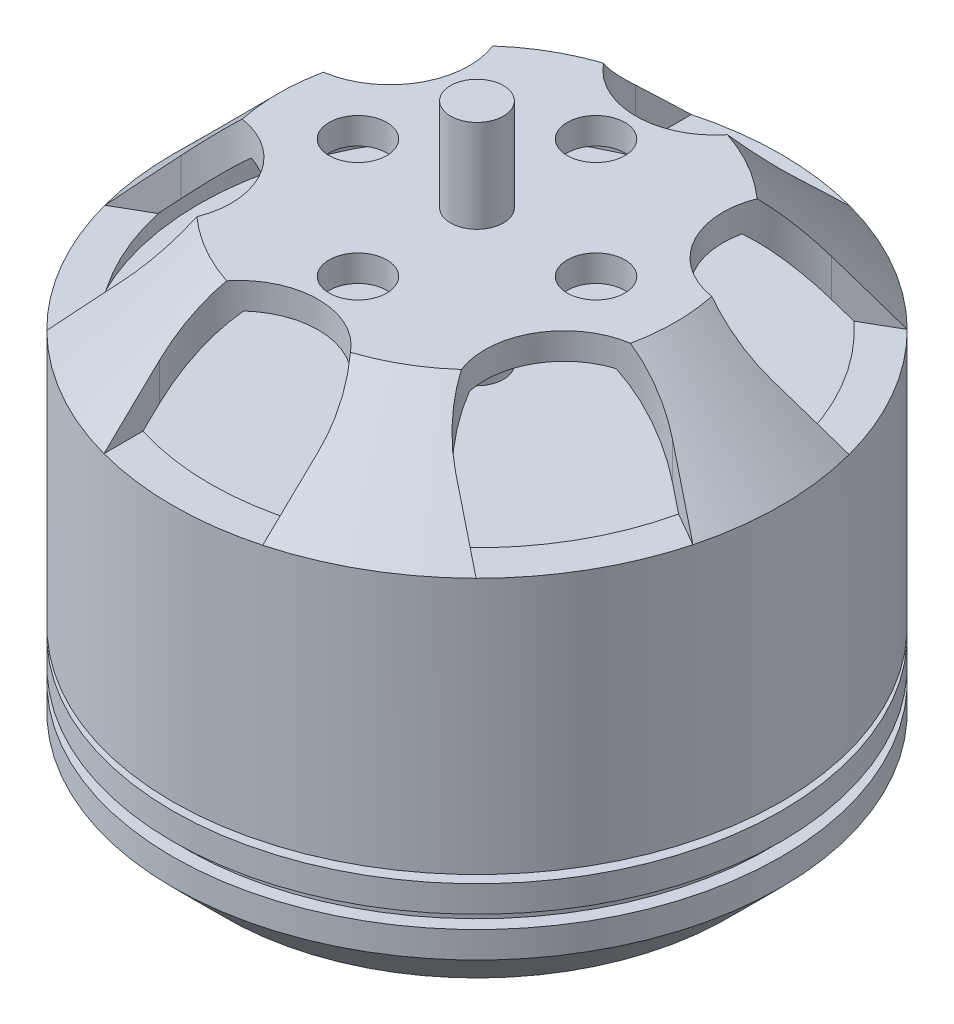
SolidWorks part; units mm, degrees
ref_plane "Front Plane" through (0, 0, 0) normal (0, 0, 1) x (1, 0, 0)
ref_plane "Top Plane" through (0, 0, 0) normal (0, 1, 0) x (1, 0, 0)
ref_plane "Right Plane" through (0, 0, 0) normal (1, 0, 0) x (0, 0, -1)
sketch "Sketch1" plane through (0, 0, 0) normal (0, 0, 1) x (1, 0, 0)
  line L0 (0, 26.2587) -> (0, 2.4587)
  line L1 (1, 4.2587) -> (9.5, 4.2587)
  line L2 (9.5, 4.2587) -> (11.5, 6.2587)
  line L3 (11.5, 6.2587) -> (11.5, 7.2587)
  line L4 (11.5, 18.7587) -> (7.5, 22.7587)
  line L5 (7.5, 22.7587) -> (1, 22.7587)
  line L6 (1, 22.7587) -> (1, 26.2587)
  line L7 (1, 26.2587) -> (0, 26.2587)
  line L9 (0, 2.4587) -> (1, 2.4587)
  line L10 (1, 2.4587) -> (1, 4.2587)
  line L18 (1, 20.7587) -> (2, 20.7587)
  line L19 (2, 20.7587) -> (2, 21.7587)
  line L20 (2, 21.7587) -> (7.0858, 21.7587)
  line L21 (7.0858, 21.7587) -> (10.5, 18.3445)
  line L22 (10.5, 18.3445) -> (10.5, 17.6371)
  line L23 (10.5, 17.6371) -> (1, 17.6371)
  line L24 (1, 17.6371) -> (1, 20.7587)
  line L25 (11.5, 7.2587) -> (11, 7.2587)
  line L26 (11, 7.2587) -> (11, 7.7587)
  line L27 (11, 7.7587) -> (11.5, 7.7587)
  line L28 (11.5, 8.7587) -> (9.5, 8.7587)
  line L29 (9.5, 8.7587) -> (9.5, 9.0587)
  line L30 (9.5, 9.0587) -> (11.5, 9.0587)
  line L31 (11.5, 9.0587) -> (11.5, 18.7587)
  line L32 (11.5, 7.7587) -> (11.5, 8.7587)
  point P27 (0, 0)
  dimension "D1" = 23.8
  dimension "D2" = 1.8
  dimension "D3" = 45
  dimension "D4" = 2
  dimension "D5" = 11.5
  dimension "D6" = 1
  dimension "D7" = 1
  dimension "D8" = 3.5
  dimension "D9" = 4
  dimension "D10" = 1
  dimension "D11" = 1
  dimension "D12" = 1
  dimension "D13" = 1
  dimension "D14" = 1
  dimension "D15" = 1
  dimension "D16" = 0.5
  dimension "D17" = 0.5
  dimension "D18" = 1
  dimension "D19" = 2
  dimension "D20" = 0.3
  dimension "D21" = 1
revolve "Revolve2" add sketch "Sketch1" angle 360 about L0
sketch "Sketch2" plane through (0, 22.7587, 0) normal (0, 1, 0) x (1, 0, 0)
  line L0 (0, 0) -> (0, 9) construction
  line L1 (-3, 9) -> (-3, 15.89)
  line L2 (3, 9) -> (3, 15.89)
  line L3 (3, 15.89) -> (-3, 15.89)
  line L4 (9.2942, 1.9019) -> (15.2611, 5.3469)
  line L5 (15.2611, 5.3469) -> (12.2611, 10.5431)
  line L6 (6.2942, 7.0981) -> (12.2611, 10.5431)
  line L7 (6.2942, -7.0981) -> (12.2611, -10.5431)
  line L8 (12.2611, -10.5431) -> (15.2611, -5.3469)
  line L9 (9.2942, -1.9019) -> (15.2611, -5.3469)
  line L10 (-3, -9) -> (-3, -15.89)
  line L11 (-3, -15.89) -> (3, -15.89)
  line L12 (3, -9) -> (3, -15.89)
  line L13 (-9.2942, -1.9019) -> (-15.2611, -5.3469)
  line L14 (-15.2611, -5.3469) -> (-12.2611, -10.5431)
  line L15 (-6.2942, -7.0981) -> (-12.2611, -10.5431)
  line L16 (-6.2942, 7.0981) -> (-12.2611, 10.5431)
  line L17 (-12.2611, 10.5431) -> (-15.2611, 5.3469)
  line L18 (-9.2942, 1.9019) -> (-15.2611, 5.3469)
  circle A0 centre (0, 0) radius 4.5 construction
  circle A1 centre (0, 0) radius 8.6644 construction
  circle A2 centre (-4.5, 0) radius 1.0898
  circle A3 centre (0, -4.5) radius 1.0898
  circle A4 centre (0, 4.5) radius 1.0898
  circle A5 centre (4.5, 0) radius 1.0898
  arc A6 (-3, 9) -> (3, 9) centre (0, 9) ccw
  arc A7 (6.2942, 7.0981) -> (9.2942, 1.9019) centre (7.7942, 4.5) ccw
  arc A8 (9.2942, -1.9019) -> (6.2942, -7.0981) centre (7.7942, -4.5) ccw
  arc A9 (3, -9) -> (-3, -9) centre (0, -9) ccw
  arc A10 (-6.2942, -7.0981) -> (-9.2942, -1.9019) centre (-7.7942, -4.5) ccw
  arc A11 (-9.2942, 1.9019) -> (-6.2942, 7.0981) centre (-7.7942, 4.5) ccw
  dimension "D1" = 9
  dimension "D3" = 2.1797
  dimension "D5" = 6
  dimension "D2" = 9
  dimension "D6" = 6.89
  dimension "D7" = 6
  dimension "D4" = 4
extrude "Cut-Extrude1" cut sketch "Sketch2" against normal blind 4
sketch "Sketch3" plane through (0, 4.2587, 0) normal (0, -1, 0) x (1, 0, 0)
  circle A0 centre (0, 0) radius 6 construction
  circle A1 centre (0, 0) radius 8 construction
  circle A2 centre (0, 6) radius 1
  circle A3 centre (0, -6) radius 1
  circle A4 centre (-8, 0) radius 1
  circle A5 centre (8, 0) radius 1
  dimension "D1" = 12
  dimension "D2" = 16
  dimension "D3" = 2
extrude "Cut-Extrude2" cut sketch "Sketch3" against normal blind 3
